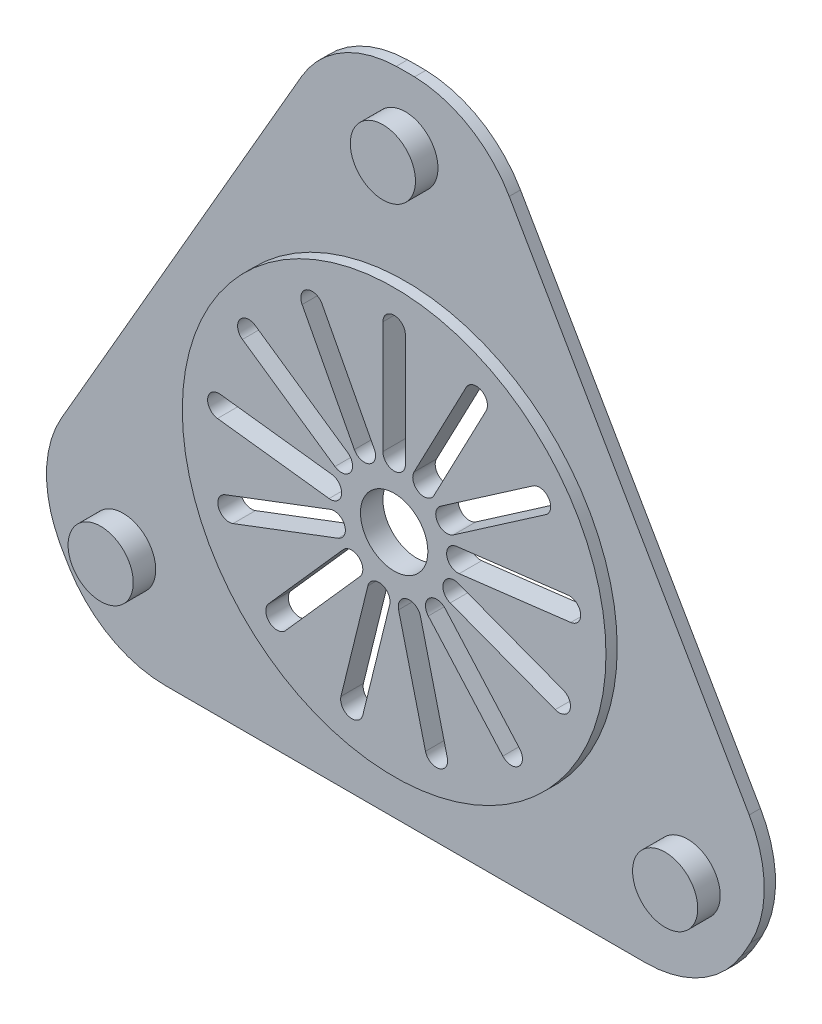
SolidWorks part; units mm, degrees
ref_plane "Спереди" through (0, 0, 0) normal (0, 0, 1) x (1, 0, 0)
ref_plane "Сверху" through (0, 0, 0) normal (0, 1, 0) x (1, 0, 0)
ref_plane "Справа" through (0, 0, 0) normal (1, 0, 0) x (0, 0, -1)
sketch "Sketch1" plane through (0, 0, 0) normal (0, 0, 1) x (1, 0, 0)
  line L0 (3.9, 6.755) -> (7.8, 0) construction
  line L2 (5.85, 10.1325) -> (11.7, 0) construction
  line L4 (7.8, 13.51) -> (15.6, 0) construction
  circle A61 centre (0, 0) radius 20
  circle A131 centre (0, 0) radius 1.25
  circle A484 centre (3.9, 0) radius 1.25
  circle A485 centre (7.8, 0) radius 1.25
  circle A486 centre (11.7, 0) radius 1.25
  circle A487 centre (15.6, 0) radius 1.25
  circle A488 centre (1.95, -3.3775) radius 1.25
  circle A489 centre (3.9, -6.755) radius 1.25
  circle A490 centre (5.85, -10.1325) radius 1.25
  circle A491 centre (7.8, -13.51) radius 1.25
  circle A492 centre (-1.95, -3.3775) radius 1.25
  circle A493 centre (-3.9, -6.755) radius 1.25
  circle A494 centre (-5.85, -10.1325) radius 1.25
  circle A495 centre (-7.8, -13.51) radius 1.25
  circle A496 centre (-3.9, 0) radius 1.25
  circle A497 centre (-7.8, 0) radius 1.25
  circle A498 centre (-11.7, 0) radius 1.25
  circle A499 centre (-15.6, 0) radius 1.25
  circle A500 centre (-1.95, 3.3775) radius 1.25
  circle A501 centre (-3.9, 6.755) radius 1.25
  circle A502 centre (-5.85, 10.1325) radius 1.25
  circle A503 centre (-7.8, 13.51) radius 1.25
  circle A504 centre (1.95, 3.3775) radius 1.25
  circle A505 centre (3.9, 6.755) radius 1.25
  circle A506 centre (5.85, 10.1325) radius 1.25
  circle A507 centre (7.8, 13.51) radius 1.25
  circle A508 centre (5.85, 3.3775) radius 1.25
  circle A509 centre (7.8, 6.755) radius 1.25
  circle A510 centre (9.75, 3.3775) radius 1.25
  circle A511 centre (11.7, 6.755) radius 1.25
  circle A512 centre (9.7491, 10.1341) radius 1.25
  circle A513 centre (13.6509, 3.3759) radius 1.25
  circle A514 centre (5.85, -3.3791) radius 1.25
  circle A515 centre (9.75, -3.3791) radius 1.25
  circle A516 centre (7.8, -6.7566) radius 1.25
  circle A517 centre (11.7, -6.7566) radius 1.25
  circle A518 centre (9.7491, -10.1356) radius 1.25
  circle A519 centre (13.6509, -3.3775) radius 1.25
  circle A520 centre (-0.0013, -6.7573) radius 1.25
  circle A521 centre (1.9487, -10.1348) radius 1.25
  circle A522 centre (-1.9513, -10.1348) radius 1.25
  circle A523 centre (-0.0013, -13.5123) radius 1.25
  circle A524 centre (-3.9032, -13.5123) radius 1.25
  circle A525 centre (3.9005, -13.5123) radius 1.25
  circle A526 centre (-5.8527, -3.3791) radius 1.25
  circle A527 centre (-7.8027, -6.7566) radius 1.25
  circle A528 centre (-9.7527, -3.3791) radius 1.25
  circle A529 centre (-11.7027, -6.7566) radius 1.25
  circle A530 centre (-13.6536, -3.3775) radius 1.25
  circle A531 centre (-9.7518, -10.1356) radius 1.25
  circle A532 centre (-5.8527, 3.3775) radius 1.25
  circle A533 centre (-9.7527, 3.3775) radius 1.25
  circle A534 centre (-7.8027, 6.755) radius 1.25
  circle A535 centre (-11.7027, 6.755) radius 1.25
  circle A536 centre (-9.7518, 10.1341) radius 1.25
  circle A537 centre (-13.6536, 3.3759) radius 1.25
  circle A538 centre (-0.0014, 6.7558) radius 1.25
  circle A539 centre (-1.9514, 10.1333) radius 1.25
  circle A540 centre (1.9486, 10.1333) radius 1.25
  circle A541 centre (-0.0014, 13.5108) radius 1.25
  circle A542 centre (3.9005, 13.5108) radius 1.25
  circle A543 centre (-3.9032, 13.5108) radius 1.25
  circle A544 centre (13.65, -1.1258) radius 2.2517 construction
  circle A545 centre (11.7009, -4.5044) radius 2.2522 construction
  circle A546 centre (9.75, -7.8834) radius 2.2522 construction
  circle A547 centre (7.7987, -11.2591) radius 2.2509 construction
  circle A548 centre (13.65, -1.1258) radius 0.65
  circle A549 centre (11.7009, -4.5044) radius 0.65
  circle A550 centre (9.75, -7.8834) radius 0.65
  circle A551 centre (7.7987, -11.2591) radius 0.65
  circle A552 centre (9.75, -1.1258) radius 0.65
  circle A553 centre (7.8009, -4.5044) radius 0.65
  circle A554 centre (5.85, -7.8834) radius 0.65
  circle A555 centre (3.8987, -11.2591) radius 0.65
  circle A556 centre (5.85, -1.1258) radius 0.65
  circle A557 centre (3.9009, -4.5044) radius 0.65
  circle A558 centre (1.95, -7.8834) radius 0.65
  circle A559 centre (-0.0013, -11.2591) radius 0.65
  circle A560 centre (1.95, -1.1258) radius 0.65
  circle A561 centre (0.0009, -4.5044) radius 0.65
  circle A562 centre (-1.95, -7.8834) radius 0.65
  circle A563 centre (-3.9013, -11.2591) radius 0.65
  circle A564 centre (-1.95, -1.1258) radius 0.65
  circle A565 centre (-3.8991, -4.5044) radius 0.65
  circle A566 centre (-5.85, -7.8834) radius 0.65
  circle A567 centre (-7.8013, -11.2591) radius 0.65
  circle A568 centre (-5.85, -1.1258) radius 0.65
  circle A569 centre (-7.7991, -4.5044) radius 0.65
  circle A570 centre (-9.75, -7.8834) radius 0.65
  circle A572 centre (-9.75, -1.1258) radius 0.65
  circle A573 centre (-11.6991, -4.5044) radius 0.65
  circle A576 centre (-13.65, -1.1258) radius 0.65
  circle A587 centre (0, 2.2517) radius 2.2517 construction
  circle A588 centre (0, 2.2517) radius 0.65
  circle A589 centre (3.9, 2.2517) radius 0.65
  circle A590 centre (7.8, 2.2517) radius 0.65
  circle A591 centre (11.7, 2.2517) radius 0.65
  circle A592 centre (15.6, 2.2517) radius 0.65
  circle A593 centre (1.9491, 5.6297) radius 2.2522 construction
  circle A594 centre (1.9491, 5.6297) radius 0.65
  circle A595 centre (5.8491, 5.6297) radius 0.65
  circle A596 centre (9.7491, 5.6297) radius 0.65
  circle A597 centre (13.6491, 5.6297) radius 0.65
  circle A598 centre (3.8991, 9.0072) radius 2.2522 construction
  circle A599 centre (3.8991, 9.0072) radius 0.65
  circle A600 centre (7.7991, 9.0072) radius 0.65
  circle A601 centre (11.6991, 9.0072) radius 0.65
  circle A602 centre (5.85, 12.3842) radius 2.2517 construction
  circle A603 centre (5.85, 12.3842) radius 0.65
  circle A604 centre (9.75, 12.3842) radius 0.65
  circle A605 centre (5.85, -14.6358) radius 0.65
  circle A606 centre (1.9509, -14.6353) radius 0.65
  circle A607 centre (-1.9491, -14.6353) radius 0.65
  circle A608 centre (-5.85, -14.6358) radius 0.65
  circle A609 centre (-15.6, 2.2517) radius 0.65
  circle A610 centre (-13.65, 5.6281) radius 0.65
  circle A611 centre (-11.7, 9.0056) radius 0.65
  circle A612 centre (-9.75, 12.3842) radius 0.65
  circle A613 centre (-5.85, 12.3842) radius 0.65
  circle A614 centre (-1.95, 12.3842) radius 0.65
  circle A615 centre (1.95, 12.3842) radius 0.65
  circle A616 centre (-7.8, 9.0056) radius 0.65
  circle A617 centre (-9.75, 5.6281) radius 0.65
  circle A618 centre (-11.7, 2.2517) radius 0.65
  circle A619 centre (-3.9, 9.0056) radius 0.65
  circle A620 centre (-5.85, 5.6281) radius 0.65
  circle A621 centre (-7.8, 2.2517) radius 0.65
  circle A622 centre (0, 9.0056) radius 0.65
  circle A623 centre (-1.95, 5.6281) radius 0.65
  circle A624 centre (-3.9, 2.2517) radius 0.65
  circle A625 centre (-15.5991, -4.5044) radius 0.65
  circle A626 centre (-13.65, -7.8834) radius 0.65
  circle A627 centre (-17.55, -7.8834) radius 0.65
  circle A628 centre (-19.5013, -11.2591) radius 0.65
  circle A629 centre (-15.6013, -11.2591) radius 0.65
  circle A630 centre (-11.7013, -11.2591) radius 0.65
  point P51 (0, 0)
  point P125 (-0.0013, -0.0008)
  point P231 (0, 0)
  dimension "D1" = 5
  dimension "D3" = 6
  dimension "D5" = 8
  dimension "D7" = 4
  dimension "D11" = 4
  dimension "D2" = 6
  dimension "D6" = 5
  dimension "D8" = 3
  dimension "D9" = 2
  dimension "D4" = 1.3
  dimension "D10" = 3
ref_plane "Plane1" through (0, 0, 10) normal (0, 0, 1) x (1, 0, 0)
sketch "Sketch2" plane through (0, 0, 10) normal (0, 0, 1) x (1, 0, 0)
  line L0 (0, 15.7117) -> (0, 5.7117) construction
  line L47 (1, 15.7117) -> (1, 5.7117)
  line L53 (-1, 15.7117) -> (-1, 5.7117)
  line L56 (6.4161, 14.3768) -> (1.7689, 5.5222)
  line L59 (8.1871, 13.4473) -> (3.5398, 4.5928)
  line L62 (7.3016, 13.912) -> (2.6544, 5.0575) construction
  line L65 (12.3624, 9.7483) -> (4.1326, 4.0676)
  line L68 (13.4986, 8.1023) -> (5.2687, 2.4216)
  line L71 (12.9305, 8.9253) -> (4.7007, 3.2446) construction
  line L86 (15.4766, 2.8865) -> (5.5495, 1.6812)
  line L89 (15.7177, 0.9011) -> (5.7906, -0.3042)
  line L92 (15.5972, 1.8938) -> (5.6701, 0.6885) construction
  line L95 (15.0453, -4.6364) -> (5.6952, -1.0904)
  line L98 (14.3361, -6.5065) -> (4.986, -2.9604)
  line L101 (14.6907, -5.5715) -> (5.3406, -2.0254) construction
  line L104 (11.1673, -11.0973) -> (4.5361, -3.6122)
  line L107 (9.6703, -12.4235) -> (3.0391, -4.9384)
  line L110 (10.4188, -11.7604) -> (3.7876, -4.2753) construction
  line L113 (4.731, -15.0159) -> (2.3378, -5.3064)
  line L116 (2.7891, -15.4945) -> (0.396, -5.7851)
  line L119 (3.7601, -15.2552) -> (1.3669, -5.5458) construction
  line L120 (-2.7891, -15.4945) -> (-0.396, -5.7851)
  line L121 (-4.731, -15.0159) -> (-2.3378, -5.3064)
  line L124 (-3.7601, -15.2552) -> (-1.3669, -5.5458) construction
  line L127 (-9.6703, -12.4235) -> (-3.0391, -4.9384)
  line L130 (-11.1673, -11.0973) -> (-4.5361, -3.6122)
  line L133 (-10.4188, -11.7604) -> (-3.7876, -4.2753) construction
  line L136 (-14.3361, -6.5065) -> (-4.986, -2.9604)
  line L139 (-15.0453, -4.6364) -> (-5.6952, -1.0904)
  line L142 (-14.6907, -5.5715) -> (-5.3406, -2.0254) construction
  line L172 (-15.7177, 0.9011) -> (-5.7906, -0.3042)
  line L173 (-15.4766, 2.8865) -> (-5.5495, 1.6812)
  line L174 (-15.5972, 1.8938) -> (-5.6701, 0.6885) construction
  line L186 (-6.3905, 14.3534) -> (-2.3232, 5.2179) construction
  line L187 (-13.4986, 8.1023) -> (-5.2687, 2.4216)
  line L188 (-12.3624, 9.7483) -> (-4.1326, 4.0676)
  line L189 (-12.9305, 8.9253) -> (-4.7007, 3.2446) construction
  line L190 (-8.1871, 13.4473) -> (-3.5398, 4.5928)
  line L191 (-6.4161, 14.3768) -> (-1.7689, 5.5222)
  line L192 (-7.3016, 13.912) -> (-2.6544, 5.0575) construction
  circle A52 centre (0, 0) radius 16.85 construction
  circle A53 centre (0, 0) radius 18.85
  arc A193 (1, 15.7117) -> (-1, 15.7117) centre (0, 15.7117) ccw
  arc A198 (-1, 5.7117) -> (1, 5.7117) centre (0, 5.7117) ccw
  circle A199 centre (0, 0) radius 3
  arc A201 (8.1871, 13.4473) -> (6.4161, 14.3768) centre (7.3016, 13.912) ccw
  arc A202 (1.7689, 5.5222) -> (3.5398, 4.5928) centre (2.6544, 5.0575) ccw
  arc A203 (13.4986, 8.1023) -> (12.3624, 9.7483) centre (12.9305, 8.9253) ccw
  arc A204 (4.1326, 4.0676) -> (5.2687, 2.4216) centre (4.7007, 3.2446) ccw
  arc A205 (15.7177, 0.9011) -> (15.4766, 2.8865) centre (15.5972, 1.8938) ccw
  arc A206 (5.5495, 1.6812) -> (5.7906, -0.3042) centre (5.6701, 0.6885) ccw
  arc A207 (14.3361, -6.5065) -> (15.0453, -4.6364) centre (14.6907, -5.5715) ccw
  arc A208 (5.6952, -1.0904) -> (4.986, -2.9604) centre (5.3406, -2.0254) ccw
  arc A209 (9.6703, -12.4235) -> (11.1673, -11.0973) centre (10.4188, -11.7604) ccw
  arc A210 (4.5361, -3.6122) -> (3.0391, -4.9384) centre (3.7876, -4.2753) ccw
  arc A211 (2.7891, -15.4945) -> (4.731, -15.0159) centre (3.7601, -15.2552) ccw
  arc A212 (2.3378, -5.3064) -> (0.396, -5.7851) centre (1.3669, -5.5458) ccw
  arc A213 (-4.731, -15.0159) -> (-2.7891, -15.4945) centre (-3.7601, -15.2552) ccw
  arc A214 (-0.396, -5.7851) -> (-2.3378, -5.3064) centre (-1.3669, -5.5458) ccw
  arc A215 (-11.1673, -11.0973) -> (-9.6703, -12.4235) centre (-10.4188, -11.7604) ccw
  arc A216 (-3.0391, -4.9384) -> (-4.5361, -3.6122) centre (-3.7876, -4.2753) ccw
  arc A217 (-15.0453, -4.6364) -> (-14.3361, -6.5065) centre (-14.6907, -5.5715) ccw
  arc A218 (-4.986, -2.9604) -> (-5.6952, -1.0904) centre (-5.3406, -2.0254) ccw
  arc A229 (-15.4766, 2.8865) -> (-15.7177, 0.9011) centre (-15.5972, 1.8938) ccw
  arc A230 (-5.7906, -0.3042) -> (-5.5495, 1.6812) centre (-5.6701, 0.6885) ccw
  arc A239 (-12.3624, 9.7483) -> (-13.4986, 8.1023) centre (-12.9305, 8.9253) ccw
  arc A240 (-5.2687, 2.4216) -> (-4.1326, 4.0676) centre (-4.7007, 3.2446) ccw
  arc A241 (-6.4161, 14.3768) -> (-8.1871, 13.4473) centre (-7.3016, 13.912) ccw
  arc A242 (-3.5398, 4.5928) -> (-1.7689, 5.5222) centre (-2.6544, 5.0575) ccw
  point P2 (0, 10.7117)
  point P12 (4.978, 9.4848)
  point P19 (8.8156, 6.085)
  point P26 (10.6336, 1.2912)
  point P33 (10.0156, -3.7984)
  point P40 (7.1032, -8.0178)
  point P47 (2.5635, -10.4005)
  point P54 (-2.5635, -10.4005)
  point P61 (-7.1032, -8.0178)
  point P68 (-10.0156, -3.7984)
  point P73 (0, 0)
  point P74 (0, 0)
  point P75 (-9.2766, -5.3559)
  point P76 (-10.6336, 1.2912)
  point P80 (0, 0)
  point P86 (-10.653, -1.1197)
  point P92 (-8.8156, 6.085)
  point P99 (-10.1875, 3.3101)
  point P103 (-4.3569, 9.7857)
  point P108 (0, 0)
  point P110 (-7.9604, 7.1675)
  point P112 (-4.978, 9.4848)
  point P117 (-4.3569, 9.7857)
  dimension "D1" = 2
  dimension "D2" = 10
  dimension "D3" = 13
extrude "Boss-Extrude1" add sketch "Sketch2" against normal blind 2
sketch "Sketch3" plane through (0, 0, 8) normal (0, 0, -1) x (-1, 0, 0)
  circle A0 centre (0, 0) radius 17.6
  circle A1 centre (0, 0) radius 35
extrude "Boss-Extrude2" add sketch "Sketch3" against normal blind 1
sketch "Sketch4" plane through (0, 0, 8) normal (0, 0, -1) x (-1, 0, 0)
  circle A0 centre (0, 0) radius 29 construction
  circle A1 centre (0, 29) radius 2.9
  circle A2 centre (25.1147, -14.5) radius 2.9
  circle A3 centre (-25.1147, -14.5) radius 2.9
  point P11 (0, 0)
  dimension "D1" = 3
extrude "Boss-Extrude3" add sketch "Sketch4" against normal blind 3
sketch "Sketch6" plane through (0, 0, 9) normal (0, 0, -1) x (-1, 0, 0)
  circle A0 centre (0, 30) radius 5
  circle A2 centre (25.9808, -15) radius 5
  circle A3 centre (-25.9808, -15) radius 5
  point P10 (0, 0)
  dimension "D1" = 3
extrude "Boss-Extrude4" add sketch "Sketch6" along normal blind 1
sketch "Sketch7" plane through (0, 0, 8) normal (0, 0, -1) x (-1, 0, 0)
  line L1 (0, 46) -> (-39.8372, -23)
  line L2 (-39.8372, -23) -> (39.8372, -23)
  line L3 (39.8372, -23) -> (0, 46)
  circle A2 centre (0, 0) radius 23 construction
  circle A3 centre (0, 0) radius 59.1314
extrude "Cut-Extrude1" cut sketch "Sketch7" against normal blind 10
fillet "Fillet1" radius 10 6 edges at (-33.1095, -11.3473, 8.5) (-6.7277, 34.3473, 8.5) (26.3818, -23, 8.5) (-26.3818, -23, 8.5) (6.7277, 34.3473, 8.5) (33.1095, -11.3473, 8.5)
